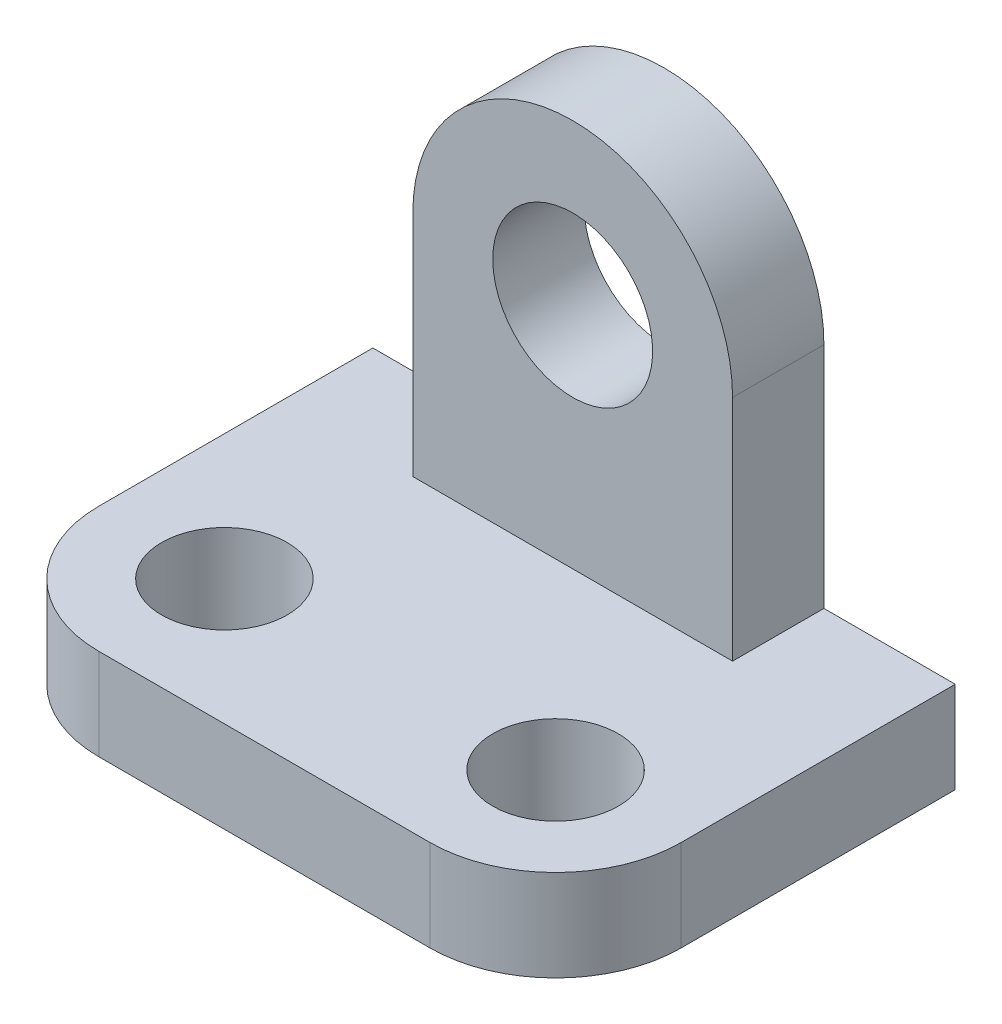
SolidWorks part; units mm, degrees
ref_plane "前视基准面" through (0, 0, 0) normal (0, 0, 1) x (1, 0, 0)
ref_plane "上视基准面" through (0, 0, 0) normal (0, 1, 0) x (1, 0, 0)
ref_plane "右视基准面" through (0, 0, 0) normal (1, 0, 0) x (0, 0, -1)
other "Configuration Table"
sketch "草图1" plane through (0, 0, 0) normal (0, 1, 0) x (1, 0, 0)
  line L0 (0, -1000) -> (0, 49000) construction
  line L1 (-14.5, -17.5) -> (14.5, -17.5)
  line L2 (-25.5, -6.5) -> (-25.5, 17.5)
  line L3 (-25.5, 17.5) -> (25.5, 17.5)
  line L4 (25.5, -6.5) -> (25.5, 17.5)
  line L5 (-25.5, -17.5) -> (25.5, 17.5) construction
  line L6 (-25.5, 17.5) -> (25.5, -17.5) construction
  circle A0 centre (14.5, -6.5) radius 5.5
  circle A1 centre (-14.5, -6.5) radius 5.5
  arc A2 (14.5, -17.5) -> (25.5, -6.5) centre (14.5, -6.5) ccw
  arc A3 (-14.5, -17.5) -> (-25.5, -6.5) centre (-14.5, -6.5) cw
  point P0 (0, 0)
  point P18 (17.24, -5.3065)
  point P19 (0, 0)
  dimension "D1" = 11
  dimension "D4" = 11
  dimension "D2" = 35
  dimension "D3" = 51
  dimension "D5" = 29
extrude "凸台-拉伸1" add sketch "草图1" along normal blind 8
sketch "草图2" plane through (0, 0, -17.5) normal (0, 0, -1) x (-1, 0, 0)
  line L0 (0, -1000) -> (0, 49000) construction
  line L1 (-14, 8) -> (14, 8)
  line L2 (-25.5, 8) -> (25.5, 8) construction
  line L3 (14, 8) -> (14, 28)
  line L4 (-14, 8) -> (-14, 28)
  line L5 (-25.5, 0) -> (25.5, 0) construction
  arc A0 (14, 28) -> (-14, 28) centre (0, 28) ccw
  circle A1 centre (0, 28) radius 7
  point P12 (0, 8)
  dimension "D1" = 14
  dimension "D2" = 14
  dimension "D3" = 28
extrude "凸台-拉伸2" add sketch "草图2" against normal blind 8
